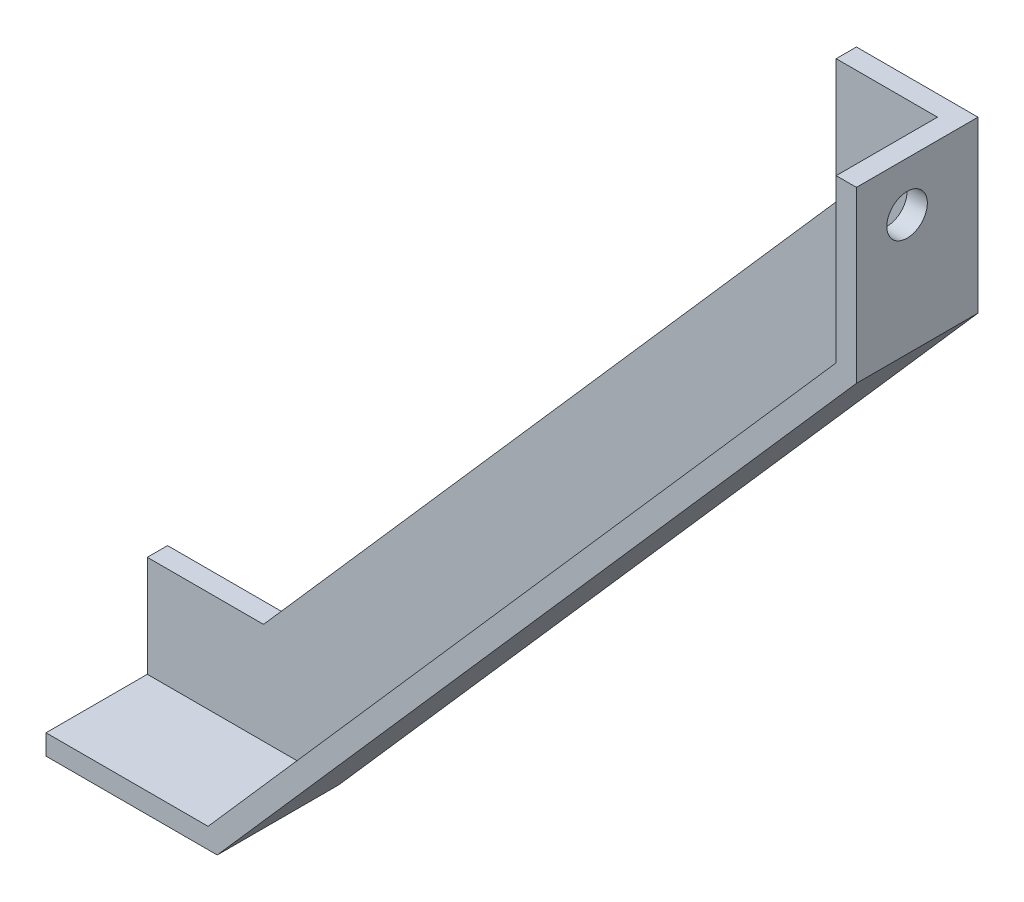
SolidWorks part; units mm, degrees
material "AISI 1010 Steel, hot rolled bar"
ref_plane "Front" through (0, 0, 0) normal (0, 0, 1) x (1, 0, 0)
ref_plane "Top" through (0, 0, 0) normal (0, 1, 0) x (1, 0, 0)
ref_plane "Right" through (0, 0, 0) normal (1, 0, 0) x (0, 0, -1)
sketch "Sketch1" plane through (0, 0, 0) normal (0, 0, 1) x (1, 0, 0)
  line L0 (0, 0) -> (0, -26.5959)
  line L1 (0, -26.5959) -> (100.1624, -140.6925)
  line L2 (100.1624, -140.6925) -> (127, -140.6925)
  line L3 (127, -140.6925) -> (127, -137.5175)
  line L4 (127, -137.5175) -> (101.6, -137.5175)
  line L5 (101.6, -137.5175) -> (3.175, -25.4)
  line L6 (3.175, -25.4) -> (3.175, 0)
  line L7 (3.175, 0) -> (0, 0)
  line L8 (101.6, -137.5175) -> (100.1624, -140.6925) construction
  line L9 (0, -26.5959) -> (3.175, -25.4) construction
  dimension "D1" = 3.175
  dimension "D2" = 3.175
  dimension "D3" = 3.175
  dimension "D4" = 140.6925
  dimension "D5" = 127
  dimension "D6" = 25.4
  dimension "D7" = 25.4
extrude "Boss-Extrude1" add sketch "Sketch1" along normal blind 19.05
sketch "Sketch2" plane through (0, 0, 0) normal (0, 0, -1) x (-1, 0, 0)
  line L0 (-127, -137.5175) -> (-127, -121.6425)
  line L1 (-127, -121.6425) -> (-108.788, -121.6425)
  line L2 (-108.788, -121.6425) -> (-19.05, -19.4205)
  line L3 (-19.05, -19.4205) -> (-19.05, 0)
  line L4 (-19.05, 0) -> (-3.175, 0)
  line L5 (-3.175, 0) -> (-3.175, -25.4)
  line L6 (-3.175, -25.4) -> (-101.6, -137.5175)
  line L15 (0, 0) -> (-3.175, 0)
  line L16 (-3.175, 0) -> (-3.175, -25.4)
  line L17 (-3.175, -25.4) -> (-101.6, -137.5175)
  line L18 (-101.6, -137.5175) -> (-127, -137.5175)
  line L19 (-127, -137.5175) -> (-127, -140.6925)
  line L20 (-127, -140.6925) -> (-100.1624, -140.6925)
  line L21 (-100.1624, -140.6925) -> (0, -26.5959)
  line L22 (0, -26.5959) -> (0, 0)
  line L24 (-3.175, 0) -> (-3.175, -25.4)
  line L25 (-3.175, -25.4) -> (-101.6, -137.5175)
  line M10 (-3.175, 0) -> (-3.175, -25.4)
  line M11 (-3.175, -25.4) -> (-101.6, -137.5175)
  line M12 (-101.6, -137.5175) -> (-127, -137.5175)
  dimension "D1" = 15.875
  dimension "D2" = 15.875
  dimension "D3" = 15.875
  dimension "D4" = 0
extrude "Boss-Extrude2" add sketch "Sketch2" against normal blind 3.175 contours L4 L3 L2 L1 L0 M12 M11 M10
sketch "Sketch3" plane through (3.175, 0, 0) normal (1, 0, 0) x (0, 0, -1)
  line L0 (-19.05, -25.4) -> (-19.05, 0) construction
  line L1 (-19.05, -140.6925) -> (0, -140.6925) construction
  circle A0 centre (-11.1125, -7.6907) radius 3.175
  dimension "D1" = 6.35
  dimension "D2" = 7.9375
  dimension "D3" = 133.0018
extrude "Cut-Extrude1" cut sketch "Sketch3" against normal through all
mirror "Mirror1" about plane through (0, 0, 19.05) normal (1, 0, 0) of "Boss-Extrude1", "Boss-Extrude2", "Cut-Extrude1"
sketch "Sketch4" plane through (0, 0, 19.05) normal (0, 0, 1) x (1, 0, 0)
  line L0 (3.175, 0) -> (-3.175, 0) construction
  line L1 (0, 0) -> (151.5292, 0)
  line L2 (0, 0) -> (0, -154.9373)
  line L3 (0, -154.9373) -> (151.5292, -154.9373)
  line L4 (151.5292, 0) -> (151.5292, -154.9373)
extrude "Cut-Extrude2" cut sketch "Sketch4" against normal blind 146.05
